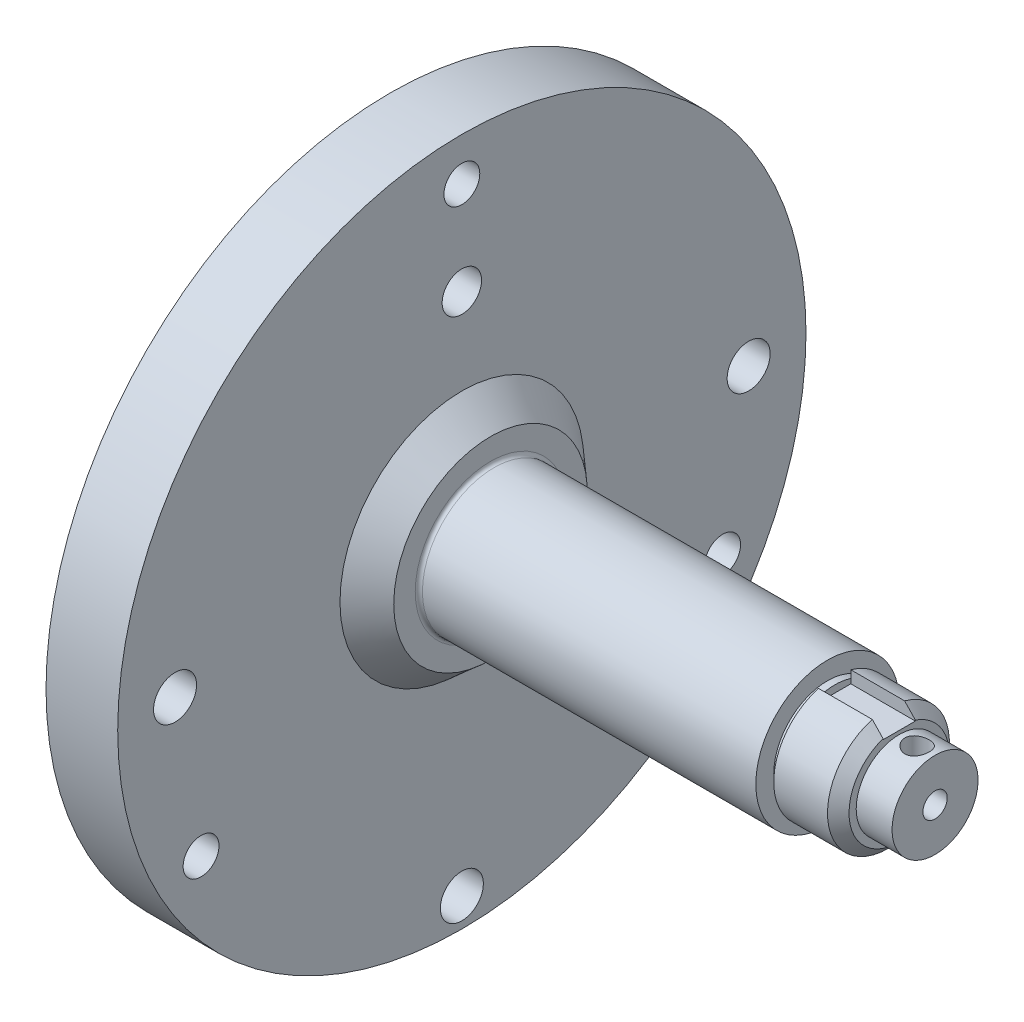
SolidWorks part; units mm, degrees
ref_plane "Plan de face" through (0, 0, 0) normal (0, 0, 1) x (1, 0, 0)
ref_plane "Plan de dessus" through (0, 0, 0) normal (0, 1, 0) x (1, 0, 0)
ref_plane "Plan de droite" through (0, 0, 0) normal (1, 0, 0) x (0, 0, -1)
sketch "Esquisse1" plane through (0, 0, 0) normal (0, 0, 1) x (1, 0, 0)
  line L0 (0, 0) -> (74.5, 0)
  line L1 (74.5, 0) -> (74.5, -6)
  line L2 (74.5, -6) -> (69.5, -6)
  line L3 (69.5, -6) -> (69.5, -7)
  line L4 (68, -8.5) -> (60.5, -8.5)
  line L5 (60.5, -8.5) -> (60.5, -7.5)
  line L6 (60.5, -7.5) -> (59.5, -7.5)
  line L7 (59.5, -7.5) -> (59.5, -10)
  line L8 (59.5, -10) -> (13, -10)
  line L9 (8.5, -17) -> (12.5, -13.5)
  line L10 (8.5, -17) -> (8.5, -48)
  line L11 (8.5, -48) -> (-1.5, -48)
  line L12 (-1.5, -48) -> (-1.5, -35)
  line L13 (-1.5, -35) -> (0, -35)
  line L14 (0, 0) -> (0, -35)
  line L15 (12.5, -13.5) -> (12.5, -10.5)
  line L16 (0, 0) -> (-50.8435, 0) construction
  line L17 (-50.8435, 0) -> (167.5419, 0) construction
  line L18 (69.5, -7) -> (68, -8.5)
  arc A0 (13, -10) -> (12.5, -10.5) centre (13, -10.5) ccw
  point P6 (69.5, -8.5)
  point P19 (12.5, -10)
  dimension "D12" = 0.5
  dimension "D1" = 1.5
  dimension "D2" = 5
  dimension "D3" = 10
  dimension "D4" = 17
  dimension "D5" = 48
  dimension "D6" = 35
  dimension "D7" = 10
  dimension "D8" = 6
  dimension "D9" = 13.5
  dimension "D10" = 4
  dimension "D11" = 74.5
  dimension "D13" = 10
  dimension "D14" = 1
  dimension "D15" = 1
  dimension "D16" = 17
  dimension "D17" = 1.5
  dimension "D18" = 45
revolve "Révolution2" add sketch "Esquisse1" angle 360 about L17
hole_wizard "Dégagement M32" positions "Esquisse3D2" profile "Esquisse2" hole size "M3" standard "Ansi Métrique"
sketch3d "Esquisse3D2"
  line L0 (74.5, 0, 0) -> (69.5, 0, 0) construction
  point P0 (0, 0, 0)
  point P3 (74.5, 0, 0)
sketch "Esquisse2" plane through (74.5, 0, 0) normal (0, 1, 0) x (0, 0, -1)
  line L0 (0, 0) -> (0, 14.9815)
  line L1 (0, 14.9815) -> (1.7, 14)
  line L2 (1.7, 14) -> (1.7, 0)
  line L5 (1.7, 0) -> (0, 0)
  line L10 (0, 14.9815) -> (-1.7, 14) construction
  line L11 (0, -6.35) -> (0, 107.95) construction
  dimension "Diamètre du perçage" = 3.4
  dimension "Profondeur du perçage" = 14
  dimension "Angle de pointe" = 120
sketch "Esquisse3" plane through (-1.5, 0, 0) normal (-1, 0, 0) x (0, 0, 1)
  line L0 (-57.7481, 0) -> (52.4783, 0) construction
  circle A1 centre (-40, 0) radius 3
  circle A2 centre (40, 0) radius 3
  dimension "D1" = 6
  dimension "D2" = 6
extrude "Enlèv. mat.-Extru.1" cut sketch "Esquisse3" against normal through all
sketch "Esquisse7" plane through (-1.5, 0, 0) normal (-1, 0, 0) x (0, 0, 1)
  line L0 (0, 0) -> (0, -56.7234) construction
  circle A2 centre (0, -44) radius 3
  dimension "D1" = 6
extrude "Enlèv. mat.-Extru.2" cut sketch "Esquisse7" against normal through all
sketch "Esquisse4" plane through (-1.5, 0, 0) normal (-1, 0, 0) x (0, 0, 1)
  line L0 (0, 54.5277) -> (0, -57.1626) construction
  circle A0 centre (0, 0) radius 42
sketch "Esquisse5" plane through (-1.5, 0, 0) normal (-1, 0, 0) x (0, 0, 1)
  line L0 (0, 0) -> (49.379, -28.509) construction
  line L1 (0, 0) -> (-48.1115, -27.7772) construction
  line L2 (0, 54.5277) -> (0, -57.1626) construction
  dimension "D1" = 60
  dimension "D2" = 60
hole_wizard "Trou taraudé M63" positions "Esquisse3D5" profile "Esquisse14" tap size "M6" standard "ISO"
sketch3d "Esquisse3D5"
  line L0 (-1.5, 54.5277, 0) -> (-1.5, -57.1626, 0) construction
  line L1 (-1.5, 0, 0) -> (-1.5, -27.7772, -48.1115) construction
  line L2 (-1.5, 0, 0) -> (-1.5, -28.509, 49.379) construction
  circle A0 centre (-1.5, 0, 0) radius 42 construction
  point P0 (-1.5, 42, 0)
  point P4 (-43.5, 0, 0)
  point P7 (-1.5, -21, -36.3731)
  point P11 (-1.5, -21, 36.3731)
sketch "Esquisse14" plane through (-1.5, 42, 0) normal (0, 1, 0) x (0, 0, 1)
  line L0 (0, 0) -> (0, 16.5022)
  line L1 (0, 16.5022) -> (2.5, 15)
  line L2 (2.5, 15) -> (2.5, 0)
  line L5 (2.5, 0) -> (0, 0)
  line L10 (0, 16.5022) -> (-2.5, 15) construction
  line L11 (0, -6.35) -> (0, 107.95) construction
  dimension "Diamètre du trou pour taraudage" = 5
  dimension "Profondeur du trou pour taraudage" = 15
  dimension "Angle de pointe" = 118
cosmetic thread "Filetage de perçage1" parameters "D1"=12, "D2"=6
cosmetic thread "Filetage de perçage2" parameters "D1"=12, "D2"=6
cosmetic thread "Filetage de perçage3" parameters "D1"=12, "D2"=6
ref_plane "Plan2" through (72, -6, 0) normal (0, -1, 0) x (0, 0, 1)
ref_plane "Plan3" through (74.5, 0, 0) normal (1, 0, 0) x (0, 0, -1)
ref_plane "Plan8" through (0, 8.5, 0) normal (0, 1, 0) x (-1, 0, 0)
hole_wizard "Dégagement M37" positions "Esquisse3D16" profile "Esquisse43" hole size "M3" standard "Ansi Métrique"
sketch3d "Esquisse3D16"
  point P0 (72, 6, 0)
  dimension "D1" = 2.5
sketch "Esquisse43" plane through (72, 6, 0) normal (1, 0, 0) x (0, 0, 1)
  line L0 (0, 0) -> (0, 4.3)
  line L1 (0, 4.3) -> (1.7, 4.3)
  line L2 (1.7, 4.3) -> (1.7, 0)
  line L5 (1.7, 0) -> (0, 0)
  line L11 (0, -6.35) -> (0, 107.95) construction
  dimension "Diamètre du perçage jusqu'au prochain" = 3.4
  dimension "Profondeur du perçage jusqu'au prochain" = 4.3
sketch "Esquisse6" plane through (0, 8.5, 0) normal (0, 1, 0) x (-1, 0, 0)
  line L0 (-60.5, -7.5) -> (-60.5, 7.5) construction
  line L1 (-60.5, 2.25) -> (-70.9477, 2.25)
  line L2 (-60.5, 2.25) -> (-60.5, -2.25)
  line L3 (-60.5, -2.25) -> (-70.9477, -2.25)
  line L4 (-70.9477, 2.25) -> (-70.9477, -2.25)
  line L6 (-88.6396, 0) -> (12.039, 0) construction
  dimension "D1" = 4.5
  dimension "D2" = 2.25
extrude "Enlèv. mat.-Extru.3" cut sketch "Esquisse6" against normal blind 2
ref_plane "Plan9" through (8.5, 0, 0) normal (1, 0, 0) x (0, 0, -1)
sketch "Esquisse8" plane through (8.5, 0, 0) normal (1, 0, 0) x (0, 0, -1)
  line L0 (0, 50.9653) -> (0, 0) construction
  circle A0 centre (0, 0) radius 29
  dimension "D1" = 58
hole_wizard "Dégagement M51" positions "Esquisse3D17" profile "Esquisse9" hole size "M5" standard "Ansi Métrique"
sketch3d "Esquisse3D17"
  line L0 (8.5, 50.9653, 0) -> (8.5, 0, 0) construction
  circle A0 centre (8.5, 0, 0) radius 29 construction
  point P0 (8.5, 29, 0)
  point P4 (37.5, 0, 0)
sketch "Esquisse9" plane through (8.5, 29, 0) normal (0, 1, 0) x (0, 0, -1)
  line L0 (0, 0) -> (0, 13.6524)
  line L1 (0, 13.6524) -> (2.75, 12)
  line L2 (2.75, 12) -> (2.75, 0)
  line L5 (2.75, 0) -> (0, 0)
  line L10 (0, 13.6524) -> (-2.75, 12) construction
  line L11 (0, -6.35) -> (0, 107.95) construction
  dimension "Diamètre du perçage" = 5.5
  dimension "Profondeur du perçage" = 12
  dimension "Angle de pointe" = 118
